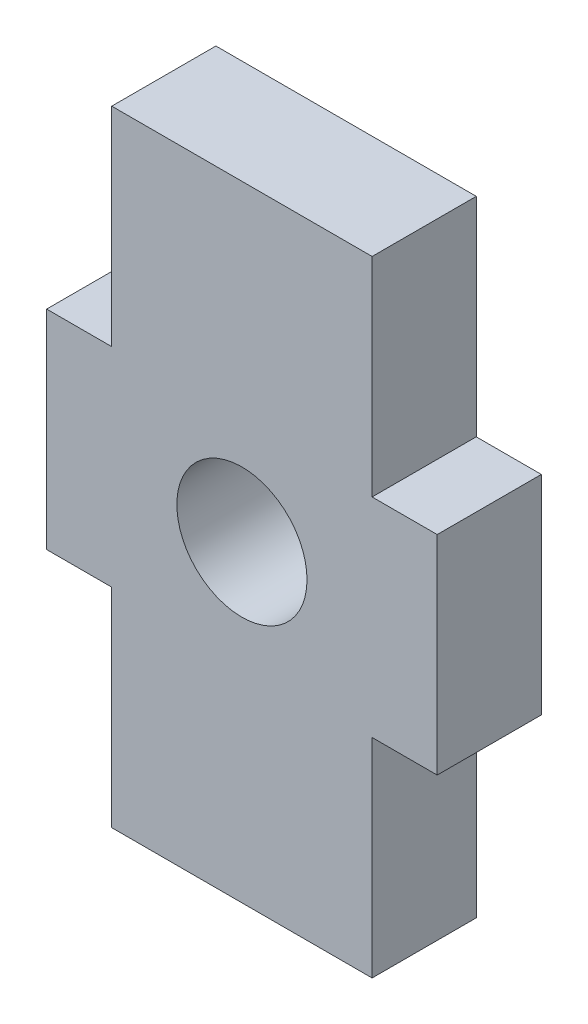
SolidWorks part; units mm, degrees
ref_plane "Front Plane" through (0, 0, 0) normal (0, 0, 1) x (1, 0, 0)
ref_plane "Top Plane" through (0, 0, 0) normal (0, 1, 0) x (1, 0, 0)
ref_plane "Right Plane" through (0, 0, 0) normal (1, 0, 0) x (0, 0, -1)
sketch "Sketch1" plane through (0, 0, 0) normal (0, 0, 1) x (1, 0, 0)
  line L0 (1952.1768, 1466.8841) -> (1957.1768, 1466.8841)
  line L1 (1952.1768, 1454.8841) -> (1957.1768, 1454.8841)
  line L3 (1957.1768, 1458.8841) -> (1957.1768, 1454.8841)
  line L4 (1957.1768, 1458.8841) -> (1958.4268, 1458.8841)
  line L5 (1958.4268, 1462.8841) -> (1958.4268, 1458.8841)
  line L6 (1957.1768, 1462.8841) -> (1957.1768, 1466.8841)
  line L7 (1957.1768, 1462.8841) -> (1958.4268, 1462.8841)
  line L37 (1952.1768, 1458.8841) -> (1950.9268, 1458.8841)
  line L40 (1952.1768, 1458.8841) -> (1952.1768, 1454.8841)
  line L127 (1952.1768, 1462.8841) -> (1950.9268, 1462.8841)
  line L130 (1952.1768, 1462.8841) -> (1952.1768, 1466.8841)
  line L131 (1950.9268, 1462.8841) -> (1950.9268, 1458.8841)
  circle A82 centre (1954.6768, 1460.8841) radius 1.25
extrude "Boss-Extrude1" add sketch "Sketch1" along normal blind 2
